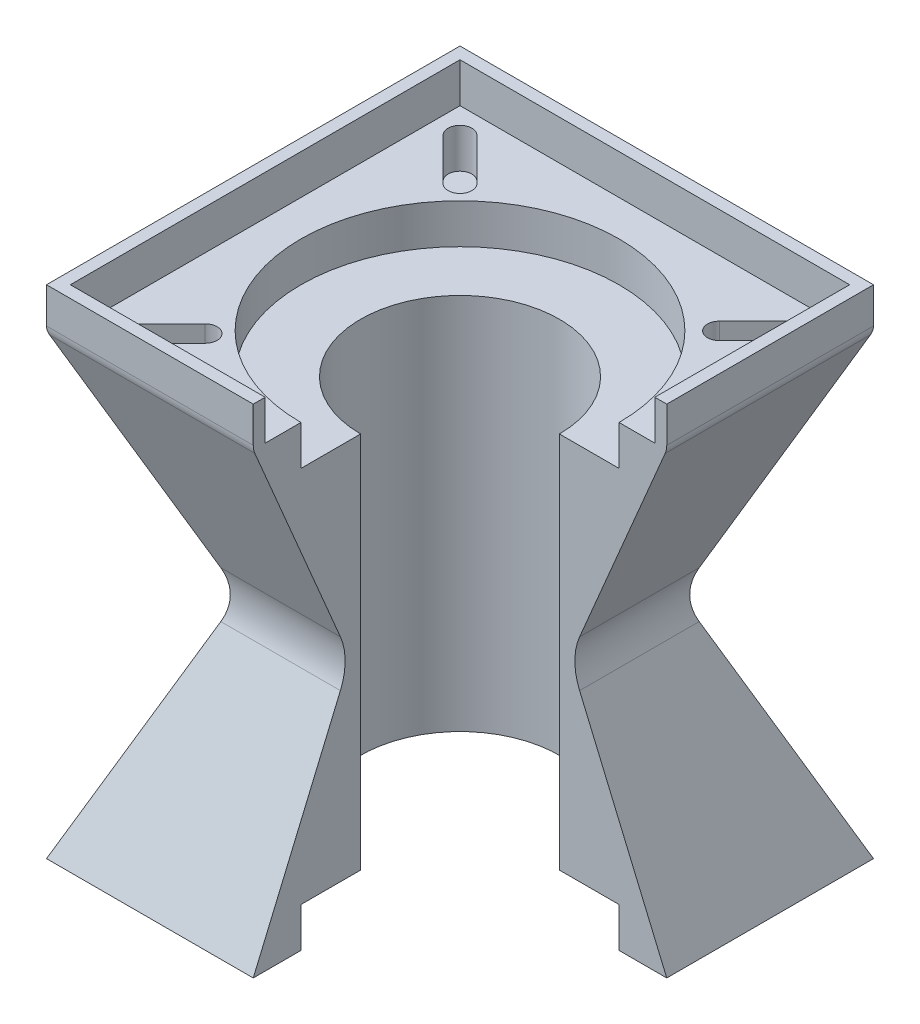
SolidWorks part; units mm, degrees
material "Cast Stainless Steel"
ref_plane "Front Plane" through (0, 0, 0) normal (0, 0, 1) x (1, 0, 0)
ref_plane "Top Plane" through (0, 0, 0) normal (0, 1, 0) x (1, 0, 0)
ref_plane "Right Plane" through (0, 0, 0) normal (1, 0, 0) x (0, 0, -1)
sketch "Sketch1" plane through (0, 0, 0) normal (0, 0, 1) x (1, 0, 0)
  line L1 (0, 0) -> (104, 0)
  line L2 (0, 0) -> (0, 115)
  line L3 (0, 115) -> (104, 115)
  line L4 (104, 0) -> (104, 115)
  dimension "D1" = 104
  dimension "D2" = 115
extrude "Boss-Extrude1" add sketch "Sketch1" along normal blind 104
sketch "Sketch2" plane through (104, 0, 0) normal (1, 0, 0) x (0, 0, -1)
  line L3 (-104, 115) -> (-79.5927, 57.5)
  line L4 (-79.5927, 57.5) -> (-104, 0)
  line L5 (-104, 0) -> (-104, 115)
  line L6 (0, 115) -> (-24.4073, 57.5)
  line L7 (-24.4073, 57.5) -> (0, 0)
  line L8 (0, 0) -> (0, 115)
  dimension "D1" = 23
extrude "Cut-Extrude1" cut sketch "Sketch2" against normal through all
sketch "Sketch3" plane through (0, 0, 0) normal (0, 0, 1) x (1, 0, 0)
  line L0 (0, 115) -> (24.4073, 57.5)
  line L1 (0, 57.5) -> (104, 57.5) construction
  line L2 (24.4073, 57.5) -> (0, 0)
  line L3 (0, 0) -> (0, 115)
  line L4 (104, 115) -> (79.5927, 57.5)
  line L5 (79.5927, 57.5) -> (104, 0)
  line L6 (104, 0) -> (104, 115)
  dimension "D1" = 23
  dimension "D2" = 23
extrude "Cut-Extrude2" cut sketch "Sketch3" along normal through all
sketch "Sketch4" plane through (0, 115, 0) normal (0, 1, 0) x (1, 0, 0)
  circle A0 centre (52, -52) radius 25
  dimension "D1" = 50
extrude "Cut-Extrude3" cut sketch "Sketch4" against normal through all
sketch "Sketch5" plane through (0, 115, 0) normal (0, 1, 0) x (1, 0, 0)
  circle A2 centre (52, -52) radius 40
  circle A3 centre (52, -52) radius 40
  dimension "D1" = 15
extrude "Cut-Extrude4" cut sketch "Sketch5" against normal blind 10
sketch "Sketch6" plane through (0, 0, 0) normal (0, -1, 0) x (1, 0, 0)
  circle A2 centre (52, 52) radius 40
  circle A3 centre (52, 52) radius 40
  dimension "D1" = 15
extrude "Cut-Extrude5" cut sketch "Sketch6" against normal blind 10
fillet "Fillet1" radius 15 4 edges at (24.4073, 57.5, 52) (52, 57.5, 24.4073) (79.5927, 57.5, 52) (52, 57.5, 79.5927)
sketch "Sketch8" plane through (0, 115, 0) normal (0, 1, 0) x (1, 0, 0)
  line L12 (101, -3) -> (3, -3)
  line L13 (3, -3) -> (3, -101)
  line L14 (3, -101) -> (101, -101)
  line L15 (101, -101) -> (101, -3)
  line L16 (101, -3) -> (3, -3)
  line L17 (3, -3) -> (3, -101)
  line L18 (3, -101) -> (101, -101)
  line L19 (101, -101) -> (101, -3)
  line L21 (0, 0) -> (104, 0)
  line L22 (0, 0) -> (0, -104)
  line L23 (0, -104) -> (104, -104)
  line L24 (104, 0) -> (104, -104)
  dimension "D1" = 3
extrude "Boss-Extrude2" add sketch "Sketch8" along normal blind 10
fillet "Fillet2" radius 5 4 edges at (52, 115, 0) (104, 115, 52) (52, 115, 104) (0, 115, 52)
sketch "Sketch11" plane through (0, 115, 0) normal (0, 1, 0) x (1, 0, 0)
  line L0 (95.2865, -8.8142) -> (84.6799, -19.4208) construction
  line L1 (97.4078, -10.9356) -> (86.8012, -21.5422)
  line L2 (93.1652, -6.6929) -> (82.5586, -17.2995)
  line L3 (9.3928, -9.3928) -> (19.9994, -19.9994) construction
  line L4 (11.5142, -7.2715) -> (22.1208, -17.8781)
  line L5 (7.2715, -11.5142) -> (17.8781, -22.1208)
  line L6 (17.6745, -17.6745) -> (19.9994, -19.9994) construction
  line L7 (95.8651, -94.7079) -> (85.2585, -84.1013) construction
  line L8 (93.7438, -96.8292) -> (83.1372, -86.2226)
  line L9 (97.9864, -92.5866) -> (87.3798, -81.98)
  line L10 (9.9715, -95.2865) -> (20.5781, -84.6799) construction
  line L11 (7.8501, -93.1652) -> (18.4567, -82.5586)
  line L12 (12.0928, -97.4078) -> (22.6994, -86.8012)
  arc A0 (97.4078, -10.9356) -> (93.1652, -6.6929) centre (95.2865, -8.8142) ccw
  arc A1 (11.5142, -7.2715) -> (7.2715, -11.5142) centre (9.3928, -9.3928) ccw
  arc A2 (17.8781, -22.1208) -> (22.1208, -17.8781) centre (19.9994, -19.9994) ccw
  arc A3 (82.5586, -17.2995) -> (86.8012, -21.5422) centre (84.6799, -19.4208) ccw
  arc A4 (93.7438, -96.8292) -> (97.9864, -92.5866) centre (95.8651, -94.7079) ccw
  arc A5 (87.3798, -81.98) -> (83.1372, -86.2226) centre (85.2585, -84.1013) ccw
  arc A6 (7.8501, -93.1652) -> (12.0928, -97.4078) centre (9.9715, -95.2865) ccw
  arc A7 (22.6994, -86.8012) -> (18.4567, -82.5586) centre (20.5781, -84.6799) ccw
  point P5 (89.9832, -14.1175)
  point P7 (14.6961, -14.6961)
  point P19 (90.5618, -89.4046)
  point P26 (15.2748, -89.9832)
  point P33 (52.629, -52.0504)
  dimension "D1" = 15
  dimension "D2" = 3
  dimension "D3" = 4
extrude "Cut-Extrude6" cut sketch "Sketch11" against normal blind 10
sketch "Sketch12" plane through (0, 115, 0) normal (0, 1, 0) x (1, 0, 0)
  line L0 (52, -52) -> (52, -104) construction
  line L2 (0, -104) -> (104, -104) construction
  line L4 (104, -104) -> (52, -104)
  line L5 (104, -104) -> (104, -52)
  line L6 (104, -52) -> (52, -52)
  line L7 (52, -104) -> (52, -52)
extrude "Cut-Extrude8" cut sketch "Sketch12" against normal through all
sketch "Sketch13" plane through (0, 125, 0) normal (0, 1, 0) x (1, 0, 0)
  line L0 (101, -52) -> (104, -52)
  line L1 (101, -101) -> (101, -3) construction
  line L2 (104, -104) -> (104, 0) construction
  line L3 (104, -52) -> (104, -104)
  line L4 (104, -104) -> (52, -103.8954)
  line L5 (52, -103.8954) -> (52, -101)
  line L6 (3, -101) -> (101, -101) construction
  line L7 (52, -101) -> (101, -101)
  line L8 (101, -101) -> (101, -52)
extrude "Cut-Extrude9" cut sketch "Sketch13" against normal through all
sketch "Sketch15" plane through (-0.2087, 0, 103.7904) normal (0.002, 0, -1) x (-1, 0, -0.002)
  line L1 (-52.2088, 115) -> (-104.2089, 115)
  line L2 (-52.2088, 115) -> (-52.2088, 125)
  line L3 (-52.2088, 125) -> (-104.2089, 125)
  line L4 (-104.2089, 115) -> (-104.2089, 125)
extrude "Cut-Extrude12" cut sketch "Sketch15" against normal through all
equation "\"A\"= 115.00"
equation "\"B\"= 104.00"
equation "\"C\"= 23.00"
